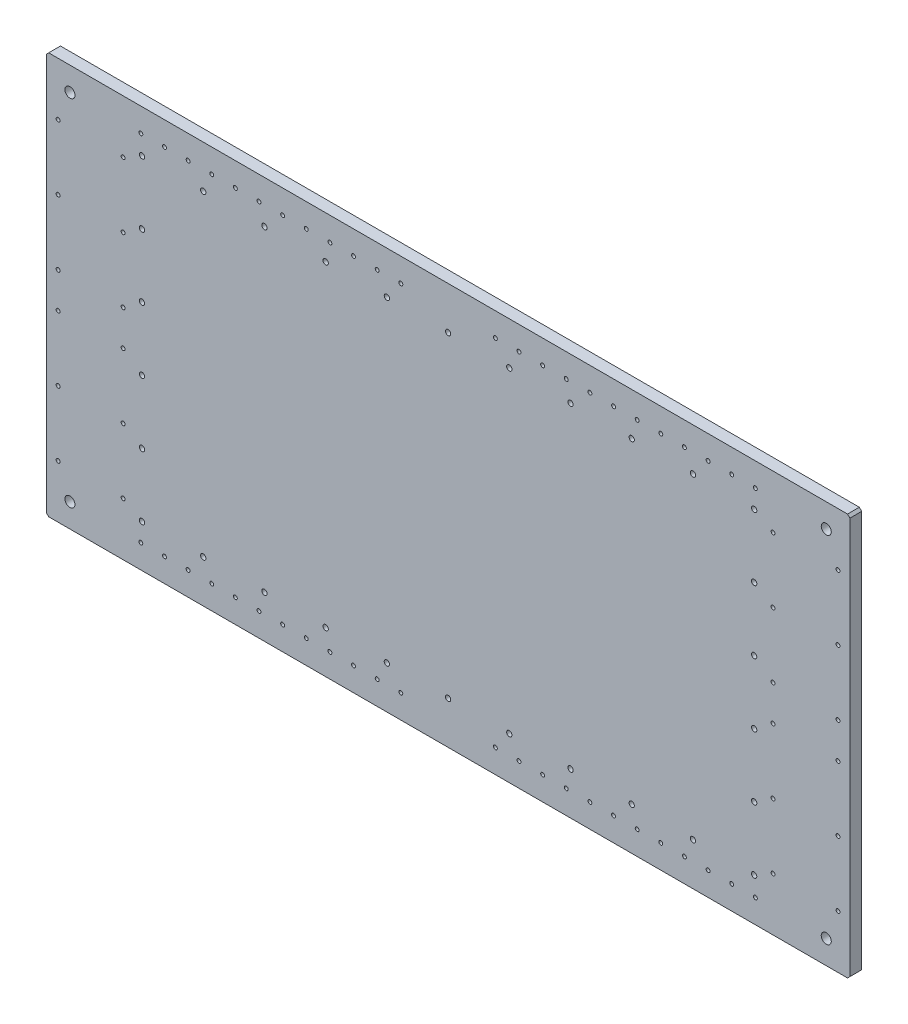
SolidWorks part; units mm, degrees
ref_plane "Front Plane" through (0, 0, 0) normal (0, 0, 1) x (1, 0, 0)
ref_plane "Top Plane" through (0, 0, 0) normal (0, 1, 0) x (1, 0, 0)
ref_plane "Right Plane" through (0, 0, 0) normal (1, 0, 0) x (0, 0, -1)
sketch "Sketch1" plane through (0, 0, 0) normal (0, 0, 1) x (1, 0, 0)
  line L0 (265, 8.25) -> (265, 140)
  line L1 (0, 0) -> (265, 0)
  line L2 (0, 0) -> (0, 140)
  line L3 (0, 140) -> (265, 140)
  line L4 (265, 0) -> (265, 3.75)
  circle A0 centre (6, 113.2) radius 2.25
  circle A1 centre (6, 59.6) radius 2.25
  circle A2 centre (6, 6) radius 2.25
  circle A3 centre (57.8, 6) radius 2.25
  circle A4 centre (109.6, 6) radius 2.25
  circle A5 centre (161.4, 6) radius 2.25
  circle A6 centre (213.2, 6) radius 2.25
  arc A7 (265, 8.25) -> (265, 3.75) centre (265, 6) ccw
  dimension "D3" = 4.5
  dimension "D4" = 4.5
  dimension "D5" = 4.5
  dimension "D6" = 4.5
  dimension "D7" = 4.5
  dimension "D8" = 4.5
  dimension "D9" = 4.5
  dimension "D10" = 6
  dimension "D11" = 6
  dimension "D12" = 6
  dimension "D13" = 6
  dimension "D14" = 6
  dimension "D15" = 6
  dimension "D16" = 6
  dimension "D17" = 6
  dimension "D18" = 4.5
  dimension "D19" = 6
  dimension "D20" = 51.8
  dimension "D21" = 51.8
  dimension "D22" = 51.8
  dimension "D23" = 51.8
  dimension "D24" = 53.6
  dimension "D25" = 53.6
  dimension "D1" = 265
  dimension "D2" = 140
extrude "Boss-Extrude1" add sketch "Sketch1" along normal blind 10 contours L1 L4 A7 L0 L3 L2 | A4 | A5 | A6 | A3 | A2 | A1 | A0
sketch "Sketch2" plane through (0, 0, 0) normal (-1, 0, 0) x (0, 0, 1)
  line L1 (0, 140) -> (10, 140)
  line L2 (0, 140) -> (0, 0)
  line L3 (0, 0) -> (10, 0)
  line L4 (10, 140) -> (10, 0)
extrude "Boss-Extrude2" add sketch "Sketch2" along normal blind 75
sketch "Sketch3" plane through (0, 0, 0) normal (0, -1, 0) x (1, 0, 0)
  line L1 (-75, 0) -> (265, 0)
  line L2 (-75, 0) -> (-75, 10)
  line L3 (-75, 10) -> (265, 10)
  line L4 (265, 0) -> (265, 10)
extrude "Boss-Extrude3" add sketch "Sketch3" along normal blind 30
sketch "Sketch4" plane through (0, 0, 10) normal (0, 0, 1) x (1, 0, 0)
  line L0 (-75, -30) -> (-75, 140) construction
  line L1 (265, -30) -> (-75, -30) construction
  circle A0 centre (-55, -10) radius 4.2 construction
  dimension "D1" = 8.4
  dimension "D2" = 20
  dimension "D3" = 20
sketch "Sketch9" plane through (0, 0, 10) normal (0, 0, 1) x (1, 0, 0)
  line L0 (-75, 140) -> (265, 140) construction
  line L1 (265, -30) -> (265, 3.75) construction
  circle A0 centre (225, -10) radius 1.65
  dimension "D1" = 150
  dimension "D2" = 40
  dimension "D3" = 3.3
hole_wizard "M10x1.5 Tapped Hole1" positions "3DSketch1" profile "Sketch14" tap size "M10x1.5" standard "BSI" end condition through all
sketch3d "3DSketch1"
  point P0 (-55, -10, 10)
sketch "Sketch14" plane through (-55, -10, 10) normal (1, 0, 0) x (0, -1, 0)
  line L0 (0, 0) -> (0, 10)
  line L1 (0, 10) -> (4.25, 10)
  line L2 (4.25, 10) -> (4.25, 0)
  line L5 (4.25, 0) -> (0, 0)
  line L11 (0, -6.35) -> (0, 107.95) construction
  dimension "Thru Tap Drill Dia." = 8.5
  dimension "Thru Tap Drill Depth" = 10
cosmetic thread "Hole Thread1" parameters "D2"=10
hole_wizard "M4x0.7 Tapped Hole1" positions "3DSketch2" profile "Sketch15" tap size "M4x0.7" standard "BSI" end condition through all
sketch3d "3DSketch2"
  point P0 (225, -10, 10)
sketch "Sketch15" plane through (225, -10, 10) normal (1, 0, 0) x (0, -1, 0)
  line L0 (0, 0) -> (0, 10)
  line L1 (0, 10) -> (1.65, 10)
  line L2 (1.65, 10) -> (1.65, 0)
  line L5 (1.65, 0) -> (0, 0)
  line L11 (0, -6.35) -> (0, 107.95) construction
  dimension "Thru Tap Drill Dia." = 3.3
  dimension "Thru Tap Drill Depth" = 10
cosmetic thread "Hole Thread2" parameters "D2"=4
pattern_linear "LPattern1" count 12 spacing 20 along (-1, 0, 0) of "M4x0.7 Tapped Hole1"
sketch "Sketch13" plane through (0, 0, 10) normal (0, 0, 1) x (1, 0, 0)
  line L0 (-75, -30) -> (-75, 140) construction
  line L1 (-75, 140) -> (265, 140) construction
  circle A0 centre (-65, 125) radius 1.65
  circle A2 centre (-10, 125) radius 1.65
  circle A3 centre (-65, 70) radius 1.65
  circle A4 centre (-10, 70) radius 1.65
  circle A5 centre (-65, 15) radius 1.65
  circle A6 centre (-10, 15) radius 1.65
  dimension "D1" = 3.3
  dimension "D3" = 3.3
  dimension "D4" = 10
  dimension "D9" = 15
  dimension "D12" = 15
  dimension "D2" = 55
  dimension "D5" = 3
hole_wizard "M4x0.7 Tapped Hole2" positions "3DSketch3" profile "Sketch16" tap size "M4x0.7" standard "BSI" end condition through all
sketch3d "3DSketch3"
  point P0 (-10, 125, 10)
  point P3 (-10, 70, 10)
  point P6 (-10, 15, 10)
  point P9 (-65, 125, 10)
  point P12 (-65, 70, 10)
  point P15 (-65, 15, 10)
sketch "Sketch16" plane through (-10, 125, 10) normal (1, 0, 0) x (0, -1, 0)
  line L0 (0, 0) -> (0, 10)
  line L1 (0, 10) -> (1.65, 10)
  line L2 (1.65, 10) -> (1.65, 0)
  line L5 (1.65, 0) -> (0, 0)
  line L11 (0, -6.35) -> (0, 107.95) construction
  dimension "Thru Tap Drill Dia." = 3.3
  dimension "Thru Tap Drill Depth" = 10
cosmetic thread "Hole Thread3" parameters "D2"=4
cosmetic thread "Hole Thread4" parameters "D2"=4
cosmetic thread "Hole Thread5" parameters "D2"=4
cosmetic thread "Hole Thread6" parameters "D2"=4
cosmetic thread "Hole Thread7" parameters "D2"=4
cosmetic thread "Hole Thread8" parameters "D2"=4
chamfer "Chamfer1" distance 2.5 angle 45 8 edges at (262.75, 6, 0) (215.45, 6, 0) (163.65, 6, 0) (111.85, 6, 0) (60.05, 6, 0) (8.25, 6, 0) (8.25, 59.6, 0) (8.25, 113.2, 0)
mirror "Mirror1" about plane through (265, 8.25, 10) normal (-1, 0, 0) of bodies 121 115
mirror "Mirror2" about plane through (0, 140, 10) normal (0, 1, 0) of bodies 116
ref_plane "Plane9" through (265, 0, 0) normal (1, 0, 0) x (0, 0, -1)
ref_plane "Plane10" through (0, 140, 0) normal (0, -1, 0) x (-1, 0, 0)
mirror "Mirror3" about plane through (265, 0, 0) normal (1, 0, 0) of "LPattern1", "M4x0.7 Tapped Hole2", "M4x0.7 Tapped Hole1", "M10x1.5 Tapped Hole1"
mirror "Mirror4" about plane through (0, 140, 0) normal (0, -1, 0) of "Mirror3"
chamfer "Chamfer2" distance 2 angle 45 4 edges at (605, -30, 5) (-75, 310, 5) (605, 310, 5) (-75, -30, 5)
equation "\"D3@Sketch13\"=\"D1@Sketch13\""
equation "\"D12@Sketch13\"=\"D9@Sketch13\""
